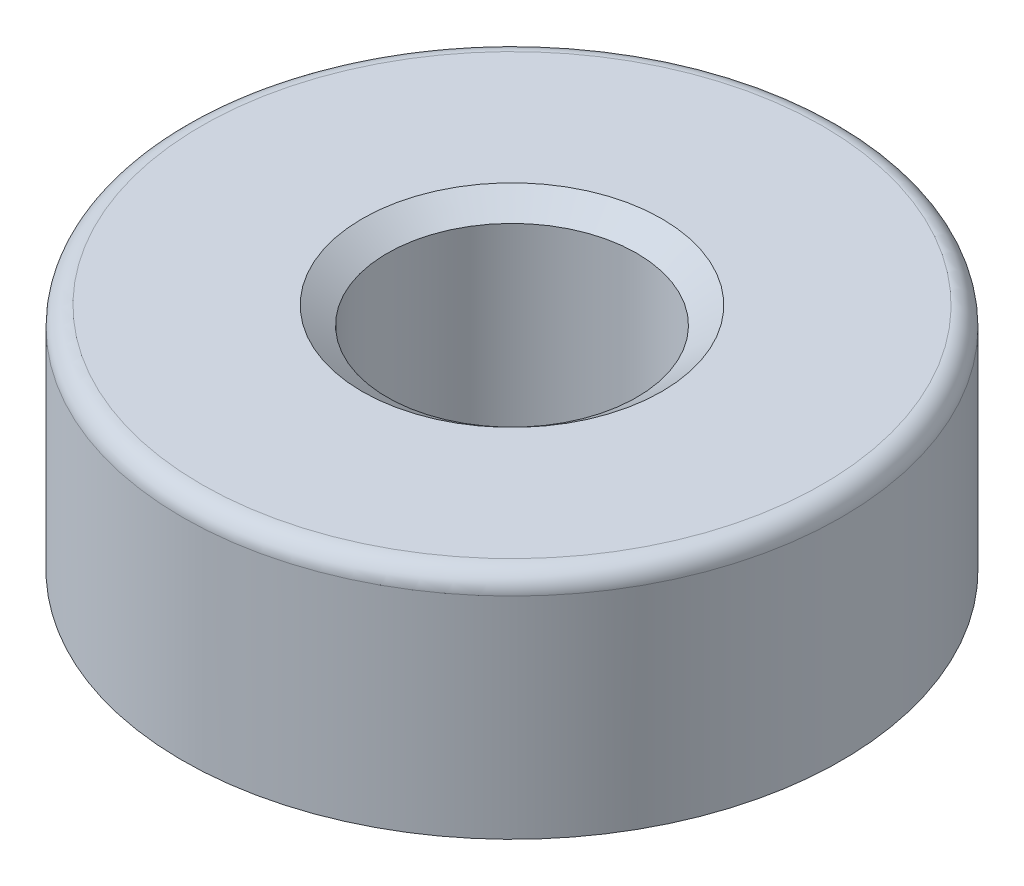
SolidWorks part; units mm, degrees
revolve "Body" add sketch "BodySke"
sketch "BodySke" plane through (0, 0, 0) normal (0, 0, 1) x (1, 0, 0)
  line L0 (4.015, 0) -> (4.8758, 0)
  line L1 (6.6, 0) -> (6.6, 4.219)
  line L2 (6.219, 4.6) -> (2.5, 4.6)
  line L3 (2.5, 4.6) -> (2.5, -1.24)
  line L4 (2.5, -1.24) -> (4.015, -1.24)
  line L5 (4.015, -1.24) -> (4.015, 0)
  line L6 (6.6, 0) -> (5.7392, -0.62)
  line L7 (1.016, 1) -> (3.6522, 1) construction
  line L8 (5.7392, -0.62) -> (4.8758, 0)
  line L9 (0, 0) -> (0, 15.24) construction
  arc A0 (6.6, 4.219) -> (6.219, 4.6) centre (6.219, 4.219) ccw
  point P14 (6.6, 4.6)
  dimension "D1" = 0.381
  dimension "E_dia" = 13.2
  dimension "C_dia" = 8.03
  dimension "A_ht" = 1.24
  dimension "T_ht" = 4.6
  dimension "Thread_min" = 5
  dimension "Advance" = 1
  dimension "Lug_minor_dia" = 9.7516
  dimension "Lug_tip_dia" = 11.4784
  dimension "Lug_ht" = 0.62
cosmetic thread "ThreadCosmetic" [suppressed]
revolve "EndChamfer" cut sketch "EndChamferSke" angle 360 about L0
sketch "EndChamferSke" plane through (0, 0, 0) normal (0, 0, 1) x (1, 0, 0)
  line L0 (0, -2.54) -> (0, 7.62) construction
  line L1 (0, 0) -> (0, 15.24) construction
  line L2 (3, -1.494) -> (3, -0.986)
  line L3 (3, -0.986) -> (2.5, -0.636)
  line L4 (2.5, -0.636) -> (2.5, -1.494)
  line L5 (2.5, -1.494) -> (3, -1.494)
  line L6 (3, 4.6) -> (2.5, 4.25)
  line L8 (2.5, 4.25) -> (2.5, 4.6)
  line L9 (3, 4.6) -> (2.5, 4.6)
  line L10 (2.5, 4.6) -> (-2.5, 4.6) construction
  line L11 (-4.015, -1.24) -> (4.015, -1.24) construction
  dimension "D1" = 0.254
  dimension "Thread_nominal" = 6
  dimension "D2" = 34.99
  dimension "Thread_min" = 5
  dimension "Inset" = 0.254
ref_plane "Plane1" through (0, 0, 0) normal (0, 0, 1) x (1, 0, 0)
ref_plane "Plane2" through (0, 0, 0) normal (0, 1, 0) x (1, 0, 0)
ref_plane "Plane3" through (0, 0, 0) normal (1, 0, 0) x (0, 0, -1)
ref_plane "Plane4" through (0, -0.5486, 0) normal (0, 1, 0) x (-1, 0, 0)
sketch "ThdSchSke" plane through (0, 0, 0) normal (0, 0, 1) x (1, 0, 0)
  line L0 (0, -5.08) -> (0, 7.62) construction
  line L1 (0, 0) -> (0, 15.24) construction
  line L2 (0, -0.986) -> (3, -0.986) construction
  line L4 (3, -0.986) -> (2.5, -0.6359)
  line L6 (3, -0.986) -> (2.5, -1.3361)
  line L7 (2.5, -0.6359) -> (2.5, -1.3361)
  line L8 (3, -0.986) -> (-3, -0.986) construction
  dimension "Thread_min" = 5
  dimension "Thread_nominal" = 6
revolve "ThreadSchematic" [suppressed] cut sketch "ThdSchSke" angle 360 about L0
pattern_linear "ThdSchPat" [suppressed]
sketch "LugGapSke" plane through (0, 0, 0) normal (0, 1, 0) x (1, 0, 0)
  line L0 (-1.0206, -4.7678) -> (-1.9146, -6.3162)
  line L1 (4.6393, -1.5) -> (6.4273, -1.5)
  line L2 (0, 0) -> (-3.8626, -6.6901) construction
  line L3 (0, 0) -> (7.366, 0) construction
  arc A0 (-1.9146, -6.3162) -> (6.4273, -1.5) centre (0, 0) ccw
  arc A1 (-1.0206, -4.7678) -> (4.6393, -1.5) centre (0, 0) ccw
  circle A2 centre (0, 0) radius 4.8758 construction
  circle A3 centre (0, 0) radius 6.6 construction
extrude "LugGap" cut sketch "LugGapSke" against normal blind 6.35
pattern_circular "LugGapPat" count 3 every 120 about axis through (0, 0, 0) along (0, 1, 0) of "LugGap"
equation "' \"A_ht@BodySke\" = 1.24"
equation "' \"C_dia@BodySke\" = 8.03"
equation "' \"E_dia@BodySke\" = 13.2"
equation "' \"T_ht@BodySke\" = 4.6"
equation "' \"Advance@BodySke\" = 1"
equation "' \"Thread_min@BodySke\" = 5"
equation "' \"Thread_nominal@ThreadCosmetic\" = 6"
equation "\"Lug_ht@BodySke\" = \"A_ht@BodySke\" / 2"
equation "\"Lug_tip_dia@BodySke\" = \"C_dia@BodySke\" + (\"E_dia@BodySke\" - \"C_dia@BodySke\" ) * 0.667"
equation "\"Lug_minor_dia@BodySke\" = \"C_dia@BodySke\" + (\"E_dia@BodySke\" - \"C_dia@BodySke\" ) * 0.333"
equation "\"Lug_wid1@LugGapSke\" = \"Thread_nominal@ThreadCosmetic\" * 0.5"
equation "\"Lug_wid2@LugGapSke\" = \"Lug_wid1@LugGapSke\""
equation "\"Thread_nominal@EndChamferSke\" = \"Thread_nominal@ThreadCosmetic\""
equation "\"Thread_min@EndChamferSke\" = \"Thread_min@BodySke\""
equation "\"D2@EndChamferSke\" = \"Vee_angle@ThdSchSke\" / 2 - 0.01"
equation "\"Thread_nominal@ThdSchSke\" = \"Thread_nominal@ThreadCosmetic\""
equation "\"Thread_min@ThdSchSke\" = \"Thread_min@BodySke\""
equation "\"Num_threads@ThdSchPat\" = int(  ( \"A_ht@BodySke\" + \"T_ht@BodySke\" - \"Inset@EndChamferSke\" ) / \"Advance@BodySke\" + 0.999 )  + 1"
equation "\"Advance@ThdSchPat\" = (  \"A_ht@BodySke\" + \"T_ht@BodySke\" - \"Inset@EndChamferSke\"  ) /  (\"Num_threads@ThdSchPat\" - 1) 'relax it"
